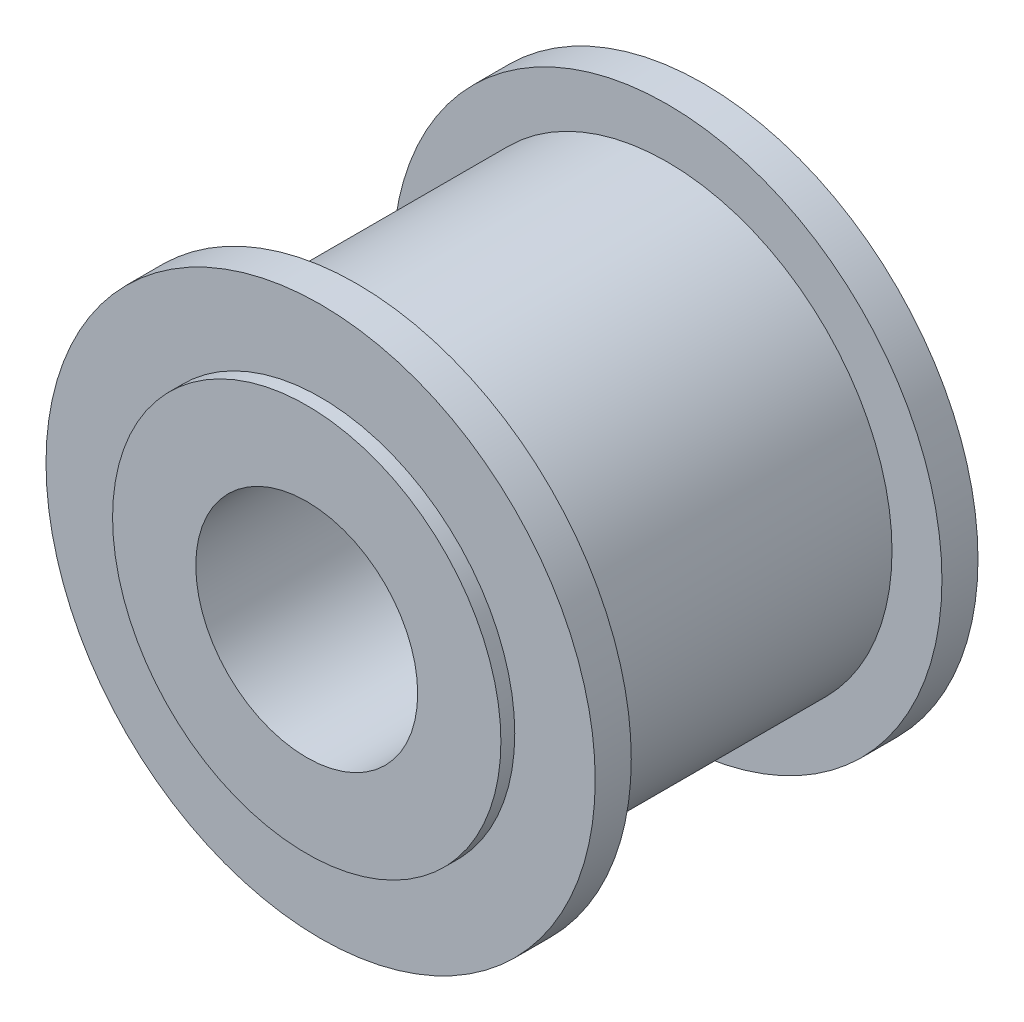
SolidWorks part; units mm, degrees
ref_plane "Front Plane" through (0, 0, 0) normal (0, 0, 1) x (1, 0, 0)
ref_plane "Top Plane" through (0, 0, 0) normal (0, 1, 0) x (1, 0, 0)
ref_plane "Right Plane" through (0, 0, 0) normal (1, 0, 0) x (0, 0, -1)
sketch "Sketch1" plane through (0, 0, 0) normal (0, 0, 1) x (1, 0, 0)
  circle A0 centre (0, 0) radius 7
  dimension "D1" = 14
extrude "Boss-Extrude1" add sketch "Sketch1" along normal blind 0.5
sketch "Sketch2" plane through (0, 0, 0.5) normal (0, 0, 1) x (1, 0, 0)
  circle A0 centre (0, 0) radius 9.9
  dimension "D1" = 19.8
extrude "Boss-Extrude2" add sketch "Sketch2" along normal blind 1.3
sketch "Sketch3" plane through (0, 0, 1.8) normal (0, 0, 1) x (1, 0, 0)
  circle A0 centre (0, 0) radius 8.1
  dimension "D1" = 16.2
extrude "Boss-Extrude3" add sketch "Sketch3" along normal blind 11.2
sketch "Sketch4" plane through (0, 0, 13) normal (0, 0, 1) x (1, 0, 0)
  circle A0 centre (0, 0) radius 9.9
extrude "Boss-Extrude4" add sketch "Sketch4" along normal blind 1.3
sketch "Sketch5" plane through (0, 0, 14.3) normal (0, 0, 1) x (1, 0, 0)
  circle A0 centre (0, 0) radius 7
  dimension "D1" = 14
extrude "Boss-Extrude5" add sketch "Sketch5" along normal blind 0.5
sketch "Sketch6" plane through (0, 0, 14.8) normal (0, 0, 1) x (1, 0, 0)
  circle A0 centre (0, 0) radius 4
  dimension "D1" = 8
extrude "Cut-Extrude1" cut sketch "Sketch6" against normal through all
